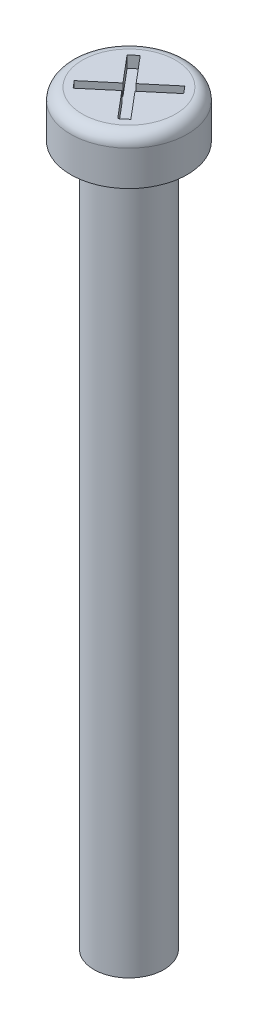
SolidWorks part; units mm, degrees
material "AISI 316 Barra de aço inoxidável recozido (SS)"
ref_plane "Plano frontal" through (0, 0, 0) normal (0, 0, 1) x (1, 0, 0)
ref_plane "Plano superior" through (0, 0, 0) normal (0, 1, 0) x (1, 0, 0)
ref_plane "Plano direito" through (0, 0, 0) normal (1, 0, 0) x (0, 0, -1)
sketch "Esboço1" plane through (0, 0, 0) normal (0, 0, 1) x (1, 0, 0)
  line L0 (0, 32) -> (2, 32)
  line L1 (2.5, 31.5) -> (2.5, 30)
  line L2 (2.5, 30) -> (1.5, 30)
  line L3 (1.5, 30) -> (1.5, 0)
  line L4 (0, 32) -> (0, -5.0364) construction
  line L5 (1.5, 0) -> (0, 0)
  line L6 (0, 32) -> (0, 0)
  arc A0 (2, 32) -> (2.5, 31.5) centre (2, 31.5) cw
  point P2 (0, 0)
  point P9 (0, -5.0364)
  point P12 (2.5, 32)
  dimension "D5" = 0.5
  dimension "D1" = 3
  dimension "D2" = 30
  dimension "D3" = 2
  dimension "D4" = 5
revolve "Revolução1" add sketch "Esboço1" angle 360 about L4
sketch "Esboço2" plane through (0, 32, 0) normal (0, 1, 0) x (1, 0, 0)
  line L0 (-1.2367, 1.1562) -> (-0.2818, 0.0239)
  line L1 (-1.1562, -1.2367) -> (-0.0239, -0.2818)
  line L2 (-0.931, 1.4141) -> (0.0239, 0.2818)
  line L3 (-1.4141, -0.931) -> (-0.2818, 0.0239)
  line L4 (-1.2367, 1.1562) -> (-0.931, 1.4141)
  line L5 (-1.0838, 1.2851) -> (1.0838, -1.2851) construction
  line L6 (-1.2851, -1.0838) -> (1.2851, 1.0838) construction
  line L7 (0.931, -1.4141) -> (1.2367, -1.1562)
  line L8 (-1.1562, -1.2367) -> (-1.4141, -0.931)
  line L9 (1.4141, 0.931) -> (1.1562, 1.2367)
  line L10 (0.0239, 0.2818) -> (1.1562, 1.2367)
  line L11 (-1.4141, -0.931) -> (1.1562, 1.2367) construction
  line L12 (-0.0239, -0.2818) -> (0.931, -1.4141)
  line L13 (-1.2367, 1.1562) -> (0.931, -1.4141) construction
  line L14 (0.2818, -0.0239) -> (1.2367, -1.1562)
  line L15 (-0.931, 1.4141) -> (1.2367, -1.1562) construction
  line L16 (0.2818, -0.0239) -> (1.4141, 0.931)
  line L17 (-1.1562, -1.2367) -> (1.4141, 0.931) construction
  point P0 (0, 0)
  dimension "D1" = 0.2
  dimension "D2" = 0.2
extrude "Corte-extrusão1" cut sketch "Esboço2" against normal blind 0.5
